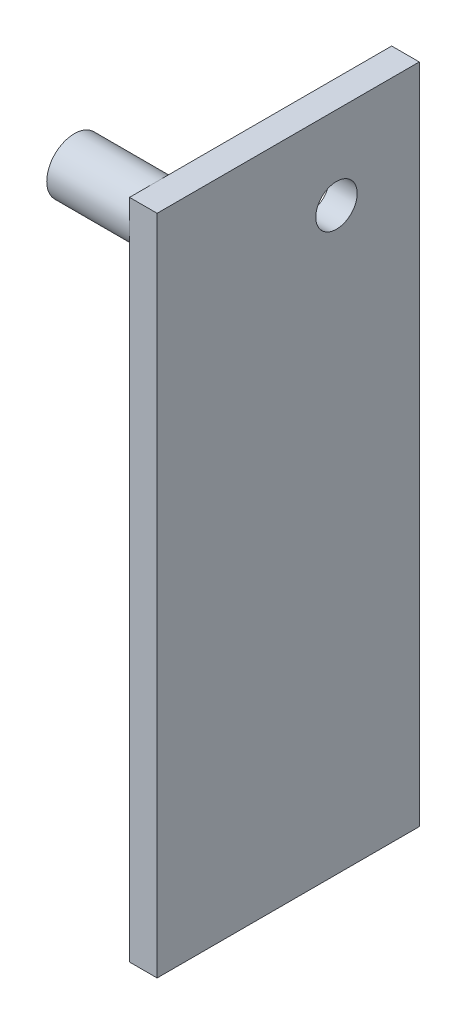
SolidWorks part; units mm, degrees
ref_plane "Front Plane" through (0, 0, 0) normal (1, 0, 0) x (0, 1, 0)
ref_plane "Top Plane" through (0, 0, 0) normal (0, 0, 1) x (0, 1, 0)
ref_plane "Right Plane" through (0, 0, 0) normal (0, 1, 0) x (-1, 0, 0)
sketch "Sketch1" plane through (0, 0, 0) normal (1, 0, 0) x (0, 1, 0)
  line L1 (0, 0) -> (48, 0)
  line L2 (0, 0) -> (0, 19)
  line L3 (0, 19) -> (48, 19)
  line L4 (48, 0) -> (48, 19)
  dimension "D1" = 48
  dimension "D2" = 19
extrude "Boss-Extrude1" add sketch "Sketch1" along normal blind 2
sketch "Sketch2" plane through (0, 0, 0) normal (-1, 0, 0) x (0, -1, 0)
  line L0 (0, 19) -> (0, 0) construction
  line L1 (0, 0) -> (-48, 0) construction
  circle A0 centre (-46, 17) radius 2
  circle A1 centre (-2, 2) radius 2
  circle A2 centre (-2, 2) radius 1
  circle A3 centre (-46, 17) radius 1
  dimension "D1" = 15
  dimension "D2" = 44
  dimension "D3" = 2
  dimension "D4" = 2
extrude "Boss-Extrude2" add sketch "Sketch2" along normal blind 6
sketch "Sketch3" plane through (0, 0, 0) normal (-1, 0, 0) x (0, -1, 0)
  line L0 (-42, 19) -> (-42, 0) construction
  line L1 (-46, 19) -> (0, 19) construction
  line L2 (-2, 0) -> (-48, 0) construction
  line L4 (-48, 0) -> (-48, 17) construction
  circle A0 centre (-42, 6) radius 1.5
  dimension "D1" = 6
  dimension "D2" = 6
extrude "Cut-Extrude1" cut sketch "Sketch3" against normal up to next
